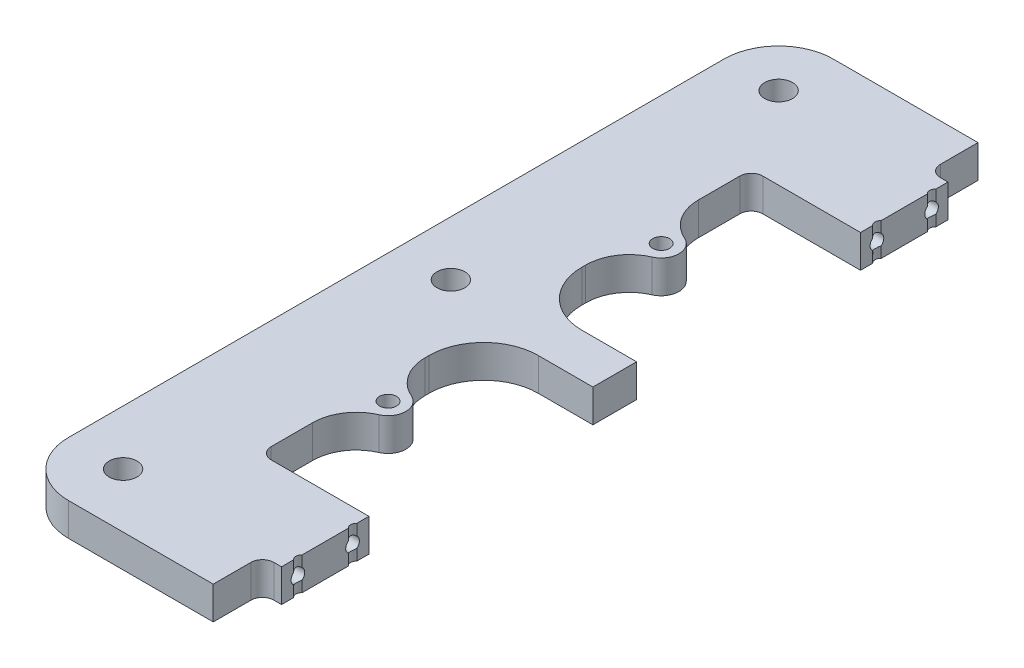
SolidWorks part; units mm, degrees
ref_plane "正面" through (0, 0, 0) normal (0, 0, 1) x (1, 0, 0)
ref_plane "平面" through (0, 0, 0) normal (0, 1, 0) x (1, 0, 0)
ref_plane "右側面" through (0, 0, 0) normal (1, 0, 0) x (0, 0, -1)
sketch "ｽｹｯﾁ1" plane through (0, 0, 0) normal (0, 1, 0) x (1, 0, 0)
  line L0 (0, -70) -> (0, 70)
  line L1 (0, 70) -> (36.5, 70)
  line L2 (36.5, 70) -> (36.5, 61)
  line L3 (36.5, 61) -> (40, 61)
  line L4 (40, 61) -> (40, 45)
  line L5 (40, 45) -> (20, 45)
  line L6 (20, 45) -> (20, -45)
  line L7 (20, 0) -> (0, 0) construction
  line L8 (40, -45) -> (20, -45)
  line L9 (40, -61) -> (40, -45)
  line L10 (36.5, -61) -> (40, -61)
  line L11 (36.5, -70) -> (36.5, -61)
  line L12 (0, -70) -> (36.5, -70)
  dimension "D1" = 140
  dimension "D2" = 9
  dimension "D3" = 3.5
  dimension "D4" = 25
  dimension "D5" = 40
  dimension "D6" = 20
extrude "ﾎﾞｽ - 押し出し1" add sketch "ｽｹｯﾁ1" along normal blind 6
sketch "ｽｹｯﾁ2" plane through (40, 0, 0) normal (1, 0, 0) x (0, 0, -1)
  line L0 (65, 6) -> (65, 0) construction
  line L1 (61, 6) -> (70, 6) construction
  line L2 (61, 0) -> (70, 0) construction
  line L3 (48, 6) -> (48, 0) construction
  line L4 (45, 6) -> (61, 6) construction
  line L5 (45, 0) -> (61, 0) construction
  line L6 (70, 6) -> (70, 0) construction
  line L7 (0, 0) -> (0, 6) construction
  line L8 (-45, 6) -> (45, 6) construction
  line L9 (58, 6) -> (58, 0) construction
  line L10 (53, 6) -> (53, 0) construction
  line L11 (48, 3) -> (53, 3) construction
  line L12 (53, 3) -> (58, 3) construction
  circle A0 centre (65, 3) radius 1.25 construction
  circle A1 centre (48, 3) radius 1.25
  circle A2 centre (58, 3) radius 1.25
  circle A3 centre (-48, 3) radius 1.25
  circle A4 centre (-58, 3) radius 1.25
  circle A5 centre (-65, 3) radius 1.25 construction
  dimension "D1" = 2.5
  dimension "D2" = 2.5
  dimension "D5" = 2.5
  dimension "D3" = 22
  dimension "D4" = 5
extrude "ｶｯﾄ - 押し出し1" cut sketch "ｽｹｯﾁ2" against normal blind 10
sketch "ｽｹｯﾁ3" plane through (0, 6, 0) normal (0, 1, 0) x (1, 0, 0)
  line L0 (36.5, 65) -> (37.2, 65) construction
  line L1 (36.5, 61) -> (36.5, 70) construction
  line L2 (40, 48) -> (40.7, 48) construction
  line L3 (40.7, 58) -> (40, 58) construction
  line L4 (40, 45) -> (40, 61) construction
  line L5 (36.5, 70) -> (0, 70) construction
  line L6 (40, 53) -> (40.7, 53) construction
  line L7 (40, 58) -> (40, 53) construction
  line L8 (40, 53) -> (40, 48) construction
  line L9 (0, 0) -> (20, 0) construction
  line L10 (20, -45) -> (20, 45) construction
  circle A0 centre (37.2, 65) radius 1.05 construction
  circle A1 centre (40.7, 58) radius 1.05
  circle A2 centre (40.7, 48) radius 1.05
  circle A3 centre (40.7, -48) radius 1.05
  circle A4 centre (40.7, -58) radius 1.05
  circle A5 centre (37.2, -65) radius 1.05 construction
  dimension "D3" = 2.1
  dimension "D1" = 5
  dimension "D2" = 22
  dimension "D4" = 0.7
extrude "ｶｯﾄ - 押し出し2" cut sketch "ｽｹｯﾁ3" against normal through all
sketch "ｽｹｯﾁ4" plane through (0, 6, 0) normal (0, 1, 0) x (1, 0, 0)
  line L0 (10, 70) -> (10, -70) construction
  line L1 (36.5, 70) -> (0, 70) construction
  line L2 (0, -70) -> (36.5, -70) construction
  line L3 (0, 0) -> (10, 0) construction
  line L4 (10, 0) -> (20, 0) construction
  line L5 (20, -45) -> (20, 45) construction
  circle A0 centre (10, 0) radius 2.55
  circle A1 centre (10, 60) radius 2.55
  circle A2 centre (10, -60) radius 2.55
  dimension "D1" = 5.1
  dimension "D2" = 10
  dimension "D3" = 10
extrude "ｶｯﾄ - 押し出し3" cut sketch "ｽｹｯﾁ4" against normal through all
fillet "ﾌｨﾚｯﾄ1" radius 2.1 4 edges at (36.5, 3, -61) (20, 3, -45) (20, 3, 45) (36.5, 3, 61)
sketch "ｽｹｯﾁ5" plane through (20, 0, 0) normal (1, 0, 0) x (0, 0, -1)
  line L0 (-42.9, 0) -> (42.9, 0) construction
  line L1 (-4, 6) -> (4, 6)
  line L2 (-4, 6) -> (-4, 0)
  line L3 (-4, 0) -> (4, 0)
  line L4 (4, 6) -> (4, 0)
  line L5 (-4, 6) -> (4, 0) construction
  line L6 (-4, 0) -> (4, 6) construction
  line L7 (-42.9, 6) -> (42.9, 6) construction
  point P0 (0, 3)
  dimension "D1" = 8
extrude "ﾎﾞｽ - 押し出し2" add sketch "ｽｹｯﾁ5" along normal up to surface (20 mm away) up to face at (40, 3, -53)
fillet "ﾌｨﾚｯﾄ2" radius 10 2 edges at (20, 3, 4) (20, 3, -4)
fillet "ﾌｨﾚｯﾄ3" radius 10 2 edges at (0, 3, 70) (0, 3, -70)
sketch "ｽｹｯﾁ7" plane through (0, 6, 0) normal (0, 1, 0) x (1, 0, 0)
  line L0 (0, 0) -> (40, 0) construction
  line L1 (0, 60) -> (0, -60) construction
  line L2 (40, -4) -> (40, 4) construction
  line L3 (0, 25) -> (40.5945, 25) construction
  line L4 (23.5, 28.25) -> (20, 28.25)
  line L5 (20, 14) -> (20, 42.9) construction
  line L6 (20, 28.25) -> (20, 21.75)
  line L7 (20, 21.75) -> (23.5, 21.75)
  line L8 (0, -25) -> (40.5945, -25) construction
  line L9 (20, -21.75) -> (23.5, -21.75)
  line L10 (20, -28.25) -> (20, -21.75)
  line L11 (23.5, -28.25) -> (20, -28.25)
  circle A0 centre (23.5, 25) radius 1.55
  arc A1 (23.5, 28.25) -> (23.5, 21.75) centre (23.5, 25) cw
  arc A2 (23.5, -28.25) -> (23.5, -21.75) centre (23.5, -25) ccw
  circle A3 centre (23.5, -25) radius 1.55
  dimension "D1" = 3.1
  dimension "D2" = 6.5
  dimension "D3" = 3.5
  dimension "D4" = 25
extrude "ﾎﾞｽ - 押し出し3" add sketch "ｽｹｯﾁ7" against normal through all
fillet "ﾌｨﾚｯﾄ4" radius 8 4 edges at (20, 3, 28.25) (20, 3, 21.75) (20, 3, -28.25) (20, 3, -21.75)
sketch "ｽｹｯﾁ8" plane through (0, 0, 0) normal (0, 1, 0) x (1, 0, 0)
  circle A0 centre (23.5, 25) radius 3.25
  circle A1 centre (23.5, -25) radius 3.25
  arc A2 (24.8, 22.0213) -> (24.8, 27.9787) centre (23.5, 25) ccw construction
  arc A3 (24.8, -27.9787) -> (24.8, -22.0213) centre (23.5, -25) ccw construction
extrude "ｶｯﾄ - 押し出し4" [suppressed] cut sketch "ｽｹｯﾁ8" along normal blind 3
fillet "ﾌｨﾚｯﾄ5" [suppressed] radius 1
